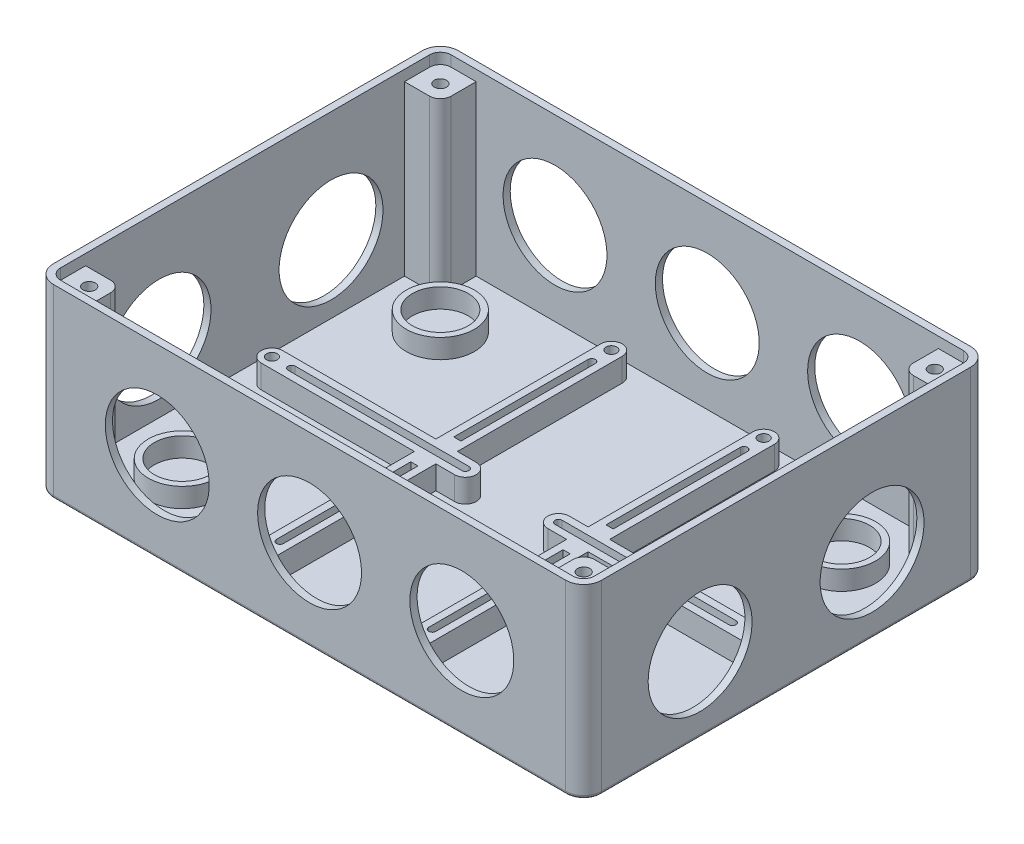
SolidWorks part; units mm, degrees
material "PBT General Purpose"
ref_plane "Front Plane" through (0, 0, 0) normal (0, 0, 1) x (1, 0, 0)
ref_plane "Top Plane" through (0, 0, 0) normal (0, 1, 0) x (1, 0, 0)
ref_plane "Right Plane" through (0, 0, 0) normal (1, 0, 0) x (0, 0, -1)
sketch "Sketch1" plane through (0, 0, 0) normal (0, 1, 0) x (1, 0, 0)
  line L0 (0, 56.5) -> (0, 0) construction
  line L1 (0, 0) -> (76.5, 0) construction
  line L2 (76.5, -51.5) -> (76.5, 51.5)
  line L3 (71.5, 56.5) -> (-71.5, 56.5)
  line L4 (-76.5, -51.5) -> (-76.5, 51.5)
  line L5 (71.5, -56.5) -> (-71.5, -56.5)
  arc A0 (76.5, 51.5) -> (71.5, 56.5) centre (71.5, 51.5) ccw
  arc A1 (-76.5, 51.5) -> (-71.5, 56.5) centre (-71.5, 51.5) cw
  arc A2 (-76.5, -51.5) -> (-71.5, -56.5) centre (-71.5, -51.5) ccw
  arc A3 (76.5, -51.5) -> (71.5, -56.5) centre (71.5, -51.5) cw
  point P17 (-76.5, 0)
  dimension "D1" = 5
  dimension "D2" = 113
  dimension "D3" = 153
extrude "Boss-Extrude1" add sketch "Sketch1" along normal blind 52
fillet "Fillet1" radius 1 8 edges at (-75.0355, 0, 55.0355) (-76.5, 0, 0) (-75.0355, 0, -55.0355) (0, 0, -56.5) (75.0355, 0, -55.0355) (76.5, 0, 0) (75.0355, 0, 55.0355) (0, 0, 56.5)
shell "Shell1" thickness 2
sketch "Sketch2" plane through (0, 0, 0) normal (0, -1, 0) x (1, 0, 0)
  line L0 (0, 64.6316) -> (0, 0) construction
  line L1 (0, 0) -> (65.5067, 0) construction
  line L2 (56, 45) -> (-56, 45)
  line L3 (56, -45) -> (-56, -45)
  line L4 (65, 36) -> (65, -36)
  line L5 (-65, 36) -> (-65, -36)
  line L6 (50.3431, 43) -> (-50.3431, 43)
  line L7 (50.3431, -43) -> (-50.3431, -43)
  line L8 (63, 30.3431) -> (63, -30.3431)
  line L9 (-63, 30.3431) -> (-63, -30.3431)
  line L11 (56, 43) -> (-56, 43) construction
  line L12 (63, 36) -> (63, -36) construction
  circle A0 centre (56, 36) radius 4
  arc A1 (65, 36) -> (56, 45) centre (56, 36) ccw
  arc A2 (50.3431, -43) -> (63, -30.3431) centre (56, -36) cw
  circle A3 centre (56, -36) radius 4
  circle A4 centre (-56, -36) radius 4
  arc A5 (-65, -36) -> (-56, -45) centre (-56, -36) ccw
  arc A6 (-50.3431, 43) -> (-63, 30.3431) centre (-56, 36) cw
  circle A7 centre (-56, 36) radius 4
  arc A8 (-65, 36) -> (-56, 45) centre (-56, 36) cw
  arc A9 (-50.3431, -43) -> (-63, -30.3431) centre (-56, -36) ccw
  arc A10 (65, -36) -> (56, -45) centre (56, -36) cw
  arc A11 (50.3431, 43) -> (63, 30.3431) centre (56, 36) ccw
  dimension "D1" = 8
  dimension "D2" = 18
  dimension "D3" = 112
  dimension "D4" = 72
  dimension "D7" = 2
  dimension "D8" = 2
  dimension "D5" = 2
  dimension "D6" = 2
extrude "Boss-Extrude2" add sketch "Sketch2" along normal blind 2.5
sketch "Sketch3" plane through (0, 0, -56.5) normal (0, 0, -1) x (-1, 0, 0)
  line L0 (0, 0) -> (0, 69.3908) construction
  line L1 (-71.5, 52) -> (71.5, 52) construction
  circle A0 centre (-42.5, 25.3) radius 14.5
  circle A1 centre (0, 25.3) radius 14.5
  circle A2 centre (42.5, 25.3) radius 14.5
  dimension "D1" = 29
  dimension "D3" = 56
  dimension "D2" = 12.2
extrude "Cut-Extrude1" cut sketch "Sketch3" against normal through all
sketch "Sketch4" plane through (0, 0, 0) normal (1, 0, 0) x (0, 0, -1)
  line L0 (0, 0) -> (0, 62.8314) construction
  line L1 (-51.5, 52) -> (51.5, 52) construction
  circle A0 centre (24, 21) radius 14.5
  circle A1 centre (-24, 21) radius 14.5
  dimension "D1" = 29
  dimension "D2" = 19
  dimension "D3" = 16.5
extrude "Cut-Extrude2" cut sketch "Sketch4" against normal through all and the other way through all
sketch "Sketch5" plane through (0, 0, 0) normal (0, -1, 0) x (1, 0, 0)
  line L0 (-44.5, 26) -> (44.5, 26)
  line L1 (-30.5, -11.5) -> (30.5, -11.5)
  line L2 (-30.5, -11.5) -> (-30.5, 11.5)
  line L3 (-30.5, 11.5) -> (30.5, 11.5)
  line L4 (30.5, -11.5) -> (30.5, 11.5)
  line L5 (-30.5, -11.5) -> (30.5, 11.5) construction
  line L6 (-30.5, 11.5) -> (30.5, -11.5) construction
  line L7 (-46.5, -28) -> (46.5, -28)
  line L8 (-46.5, -28) -> (-46.5, 28)
  line L9 (-46.5, 28) -> (46.5, 28)
  line L10 (46.5, -28) -> (46.5, 28)
  line L11 (-46.5, -28) -> (46.5, 28) construction
  line L12 (-46.5, 28) -> (46.5, -28) construction
  line L13 (44.5, -26) -> (44.5, 26)
  line L14 (-44.5, -26) -> (44.5, -26)
  line L15 (-44.5, -26) -> (-44.5, 26)
  line L16 (-28.5, 9.5) -> (28.5, 9.5)
  line L17 (28.5, -9.5) -> (28.5, 9.5)
  line L18 (-28.5, -9.5) -> (28.5, -9.5)
  line L19 (-28.5, -9.5) -> (-28.5, 9.5)
  point P0 (0, 0)
  point P6 (0, 0)
  dimension "D1" = 93
  dimension "D2" = 56
  dimension "D3" = 61
  dimension "D4" = 23
  dimension "D5" = 2
extrude "Boss-Extrude3" add sketch "Sketch5" along normal up to surface (2.5 mm away) contours L7 L10 L9 L8 L14 L15 L0 L13 | L1 L4 L3 L2 L18 L19 L16 L17 up to face at (-56, -2.5, 40)
sketch "Sketch6" plane through (0, -2.5, 0) normal (0, -1, 0) x (1, 0, 0)
  line L0 (28.5, 9.5) -> (53.1197, 33.2244)
  line L1 (53.1197, 33.2244) -> (56, 36) construction
  line L2 (28.5, -9.5) -> (53.1197, -33.2244)
  line L3 (53.1197, -33.2244) -> (56, -36) construction
  line L4 (0, 0) -> (0, -66.9433) construction
  line L5 (-28.5, 9.5) -> (-53.1197, 33.2244)
  line L6 (-28.5, -9.5) -> (-53.1197, -33.2244)
  circle A0 centre (56, 36) radius 4 construction
  circle A1 centre (56, -36) radius 4 construction
extrude "Extrude-Thin1" add sketch "Sketch6" against normal up to next thin contours L0
sketch "Sketch7" plane through (0, -2.5, 0) normal (0, -1, 0) x (1, 0, 0)
  line L0 (28.5, -9.5) -> (53.1197, -33.2244) construction
  line L1 (28.5, -9.5) -> (53.1197, -33.2244)
extrude "Extrude-Thin2" add sketch "Sketch7" against normal up to next thin
mirror "Mirror1" about plane through (0, 0, 0) normal (1, 0, 0) of "Extrude-Thin2", "Extrude-Thin1"
sketch "Sketch8" plane through (0, 2, 0) normal (0, 1, 0) x (1, 0, 0)
  line L0 (0, 70.5494) -> (0, 0) construction
  line L1 (0, 0) -> (92.2835, 0) construction
  circle A0 centre (56, 36) radius 9.5
  circle A1 centre (-56, 36) radius 9.5
  circle A2 centre (56, -36) radius 9.5
  circle A3 centre (-56, -36) radius 9.5
  dimension "D1" = 19
extrude "Extrude-Thin3" add sketch "Sketch8" along normal blind 5.4 thin thin type one direction reverse wall 1.7
sketch "Sketch9" plane through (0, 2, 0) normal (0, 1, 0) x (1, 0, 0)
  line L0 (21.25, 49) -> (21.25, -49) construction
  line L1 (13, 0) -> (67, 0) construction
  line L2 (13, 3) -> (18.25, 3)
  line L3 (13, -3) -> (18.25, -3)
  line L4 (24.25, 49) -> (24.25, 3)
  line L5 (18.25, 49) -> (18.25, 3)
  line L6 (24.25, 3) -> (67, 3)
  line L7 (24.25, -3) -> (24.25, -49)
  line L8 (18.25, -3) -> (18.25, -49)
  line L9 (24.25, -3) -> (67, -3)
  line L10 (42.5, 56.5) -> (0, 56.5) construction
  line L11 (57, 56.5) -> (28, 56.5) construction
  line L12 (14.5, 56.5) -> (-14.5, 56.5) construction
  line L13 (21.25, 56.5) -> (21.25, 49) construction
  line L14 (0, 68.5135) -> (0, -74.3134) construction
  line L15 (-24.25, -3) -> (-24.25, -49)
  line L16 (-18.25, -3) -> (-18.25, -49)
  line L17 (-13, -3) -> (-18.25, -3)
  line L18 (-13, 3) -> (-18.25, 3)
  line L19 (-18.25, 49) -> (-18.25, 3)
  line L20 (-24.25, 49) -> (-24.25, 3)
  line L21 (-24.25, 3) -> (-67, 3)
  line L22 (-24.25, -3) -> (-67, -3)
  arc A0 (13, 3) -> (13, -3) centre (13, 0) ccw
  arc A1 (67, -3) -> (67, 3) centre (67, 0) ccw
  arc A2 (24.25, 49) -> (18.25, 49) centre (21.25, 49) ccw
  arc A3 (18.25, -49) -> (24.25, -49) centre (21.25, -49) ccw
  circle A4 centre (67, 0) radius 1.5
  circle A5 centre (21.25, 49) radius 1.5
  circle A6 centre (21.25, -49) radius 1.5
  circle A7 centre (-67, 0) radius 1.5
  circle A8 centre (-21.25, 49) radius 1.5
  circle A9 centre (-21.25, -49) radius 1.5
  arc A10 (-18.25, -49) -> (-24.25, -49) centre (-21.25, -49) cw
  arc A11 (-13, 3) -> (-13, -3) centre (-13, 0) cw
  arc A12 (-24.25, 49) -> (-18.25, 49) centre (-21.25, 49) cw
  arc A13 (-67, -3) -> (-67, 3) centre (-67, 0) cw
  point P5 (38.2798, 0)
  point P10 (21.3934, 0)
  dimension "D1" = 3
  dimension "D2" = 3
  dimension "D3" = 98
  dimension "D5" = 20
  dimension "D4" = 134
extrude "Boss-Extrude4" add sketch "Sketch9" along normal blind 6.5
sketch "Sketch10" plane through (0, 8.5, 0) normal (0, 1, 0) x (1, 0, 0)
  line L0 (13, 0) -> (61.5, 0) construction
  line L1 (13, 1) -> (61.5, 1)
  line L2 (13, -1) -> (61.5, -1)
  line L3 (0, 0) -> (0, -71.6768) construction
  line L4 (-13, 0) -> (-61.5, 0) construction
  line L5 (-13, 1) -> (-61.5, 1)
  line L6 (-13, -1) -> (-61.5, -1)
  arc A0 (13, 1) -> (13, -1) centre (13, 0) ccw
  arc A1 (61.5, -1) -> (61.5, 1) centre (61.5, 0) ccw
  circle A3 centre (67, 0) radius 1.5 construction
  arc A4 (-13, 1) -> (-13, -1) centre (-13, 0) cw
  arc A5 (-61.5, -1) -> (-61.5, 1) centre (-61.5, 0) cw
  point P4 (37.25, 0)
  point P15 (-37.25, 0)
  dimension "D1" = 1
  dimension "D2" = 3
extrude "Cut-Extrude3" cut sketch "Sketch10" against normal blind 6.5
sketch "Sketch11" plane through (0, 8.5, 0) normal (0, 1, 0) x (1, 0, 0)
  line L0 (0, 64.5422) -> (0, 0) construction
  line L1 (0, 0) -> (95.9798, 0) construction
  line L2 (18.25, 3) -> (13, 3) construction
  line L3 (21.25, 49) -> (21.25, 43.5) construction
  line L4 (22.25, 43.5) -> (22.25, 6)
  line L5 (22.25, 6) -> (20.25, 6)
  line L6 (20.25, 43.5) -> (20.25, 6)
  line L7 (20.25, -43.5) -> (20.25, -6)
  line L8 (22.25, -6) -> (20.25, -6)
  line L9 (22.25, -43.5) -> (22.25, -6)
  line L10 (-20.25, -43.5) -> (-20.25, -6)
  line L11 (-22.25, -6) -> (-20.25, -6)
  line L12 (-22.25, -43.5) -> (-22.25, -6)
  line L13 (-20.25, 43.5) -> (-20.25, 6)
  line L14 (-22.25, 6) -> (-20.25, 6)
  line L15 (-22.25, 43.5) -> (-22.25, 6)
  arc A0 (22.25, 43.5) -> (20.25, 43.5) centre (21.25, 43.5) ccw
  circle A1 centre (21.25, 49) radius 1.5 construction
  arc A3 (22.25, -43.5) -> (20.25, -43.5) centre (21.25, -43.5) cw
  arc A4 (-22.25, -43.5) -> (-20.25, -43.5) centre (-21.25, -43.5) ccw
  arc A5 (-22.25, 43.5) -> (-20.25, 43.5) centre (-21.25, 43.5) cw
  dimension "D2" = 3
  dimension "D1" = 3
  dimension "D3" = 2
extrude "Cut-Extrude4" cut sketch "Sketch11" against normal blind 6.5
sketch "Sketch12" plane through (0, 2, 0) normal (0, 1, 0) x (1, 0, 0)
  line L0 (64.5, 54.5) -> (64.5, 47.5)
  line L1 (71.5, 54.5) -> (-71.5, 54.5) construction
  line L2 (67.5, 44.5) -> (74.5, 44.5)
  line L3 (74.5, -51.5) -> (74.5, 51.5) construction
  line L4 (74.5, 44.5) -> (74.5, 51.5)
  line L5 (64.5, 54.5) -> (71.5, 54.5)
  line L6 (0, 69.5623) -> (0, 0) construction
  line L7 (0, 0) -> (88.4976, 0) construction
  line L8 (64.5, -54.5) -> (71.5, -54.5)
  line L9 (74.5, -44.5) -> (74.5, -51.5)
  line L10 (67.5, -44.5) -> (74.5, -44.5)
  line L11 (64.5, -54.5) -> (64.5, -47.5)
  line L12 (-64.5, -54.5) -> (-64.5, -47.5)
  line L13 (-67.5, -44.5) -> (-74.5, -44.5)
  line L14 (-74.5, -44.5) -> (-74.5, -51.5)
  line L15 (-64.5, -54.5) -> (-71.5, -54.5)
  line L16 (-64.5, 54.5) -> (-71.5, 54.5)
  line L17 (-74.5, 44.5) -> (-74.5, 51.5)
  line L18 (-67.5, 44.5) -> (-74.5, 44.5)
  line L19 (-64.5, 54.5) -> (-64.5, 47.5)
  arc A0 (74.5, 51.5) -> (71.5, 54.5) centre (71.5, 51.5) ccw construction
  arc A1 (74.5, 51.5) -> (71.5, 54.5) centre (71.5, 51.5) ccw construction
  arc A2 (74.5, 51.5) -> (71.5, 54.5) centre (71.5, 51.5) ccw
  arc A3 (64.5, 47.5) -> (67.5, 44.5) centre (67.5, 47.5) ccw
  circle A4 centre (69, 49) radius 1.7
  circle A5 centre (69, -49) radius 1.7
  arc A6 (64.5, -47.5) -> (67.5, -44.5) centre (67.5, -47.5) cw
  arc A7 (74.5, -51.5) -> (71.5, -54.5) centre (71.5, -51.5) cw
  arc A8 (-74.5, -51.5) -> (-71.5, -54.5) centre (-71.5, -51.5) ccw
  arc A9 (-64.5, -47.5) -> (-67.5, -44.5) centre (-67.5, -47.5) ccw
  circle A10 centre (-69, -49) radius 1.7
  circle A11 centre (-69, 49) radius 1.7
  arc A12 (-64.5, 47.5) -> (-67.5, 44.5) centre (-67.5, 47.5) cw
  arc A13 (-74.5, 51.5) -> (-71.5, 54.5) centre (-71.5, 51.5) cw
  point P54 (88.0492, 2.2144)
  dimension "D1" = 3
  dimension "D5" = 98
  dimension "D6" = 3.4
  dimension "D2" = 10
  dimension "D3" = 10
  dimension "D4" = 138
extrude "Boss-Extrude5" add sketch "Sketch12" along normal blind 47
